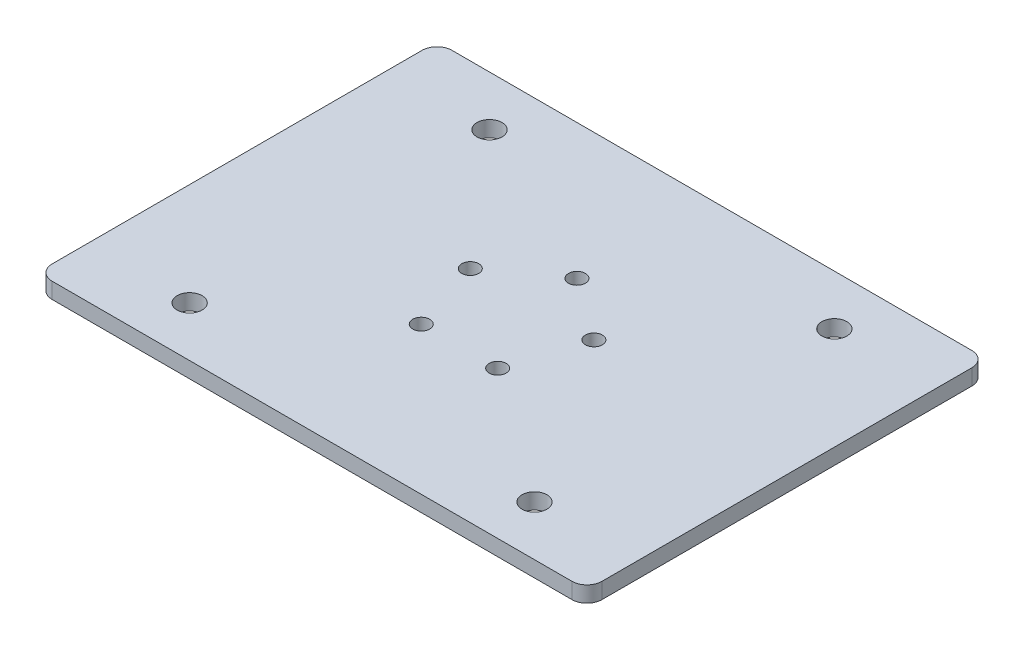
SolidWorks part; units mm, degrees
material "ABS"
ref_plane "Alzado" through (0, 0, 0) normal (0, 0, 1) x (1, 0, 0)
ref_plane "Planta" through (0, 0, 0) normal (0, 1, 0) x (1, 0, 0)
ref_plane "Vista lateral" through (0, 0, 0) normal (1, 0, 0) x (0, 0, -1)
sketch "Croquis1" plane through (0, 0, 0) normal (0, 1, 0) x (1, 0, 0)
  line L1 (52, 40) -> (-52, 40)
  line L2 (55, 37) -> (55, -37)
  line L3 (52, -40) -> (-52, -40)
  line L4 (-55, 37) -> (-55, -37)
  line L5 (55, 40) -> (-55, -40) construction
  line L6 (55, -40) -> (-55, 40) construction
  line L7 (-34.5, 30) -> (34.5, 30) construction
  line L8 (-34.5, 30) -> (-34.5, -30) construction
  line L9 (-34.5, -30) -> (34.5, -30) construction
  line L10 (34.5, 30) -> (34.5, -30) construction
  line L11 (-34.5, 30) -> (34.5, -30) construction
  line L12 (-34.5, -30) -> (34.5, 30) construction
  circle A0 centre (34.5, 30) radius 2.5
  circle A1 centre (34.5, -30) radius 2.5
  circle A2 centre (-34.5, -30) radius 2.5
  circle A3 centre (-34.5, 30) radius 2.5
  arc A4 (52, 40) -> (55, 37) centre (52, 37) cw
  arc A5 (55, -37) -> (52, -40) centre (52, -37) cw
  arc A6 (-52, -40) -> (-55, -37) centre (-52, -37) cw
  arc A7 (-52, 40) -> (-55, 37) centre (-52, 37) ccw
  point P0 (0, 0)
  point P6 (0, 0)
  dimension "D5" = 5
  dimension "D6" = 3
  dimension "D1" = 110
  dimension "D2" = 80
  dimension "D3" = 69
  dimension "D4" = 60
extrude "Saliente-Extruir1" add sketch "Croquis1" along normal mid plane 3.175
hole_wizard "Taladro de margen para M31" positions "Croquis3" profile "Croquis2" hole size "M3" standard "Ansi Metric"
sketch "Croquis3" plane through (0, 1.5875, 0) normal (0, 1, 0) x (1, 0, 0)
  circle A0 centre (0, 0) radius 13
  point P5 (0, 13)
  point P12 (12.3637, 4.0172)
  point P13 (7.6412, -10.5172)
  point P14 (-7.6412, -10.5172)
  point P15 (-12.3637, 4.0172)
  dimension "D1" = 26
  dimension "D2" = 5
sketch "Croquis2" plane through (0, 1.5875, -13) normal (1, 0, 0) x (0, 0, 1)
  line L0 (0, 0) -> (0, 11.0215)
  line L1 (0, 11.0215) -> (1.7, 10)
  line L2 (1.7, 10) -> (1.7, 0)
  line L5 (1.7, 0) -> (0, 0)
  line L10 (0, 11.0215) -> (-1.7, 10) construction
  line L11 (0, -6.35) -> (0, 107.95) construction
  dimension "Diámetro de taladro" = 3.4
  dimension "Profundidad de taladro" = 10
  dimension "Ángulo de perforador" = 118
